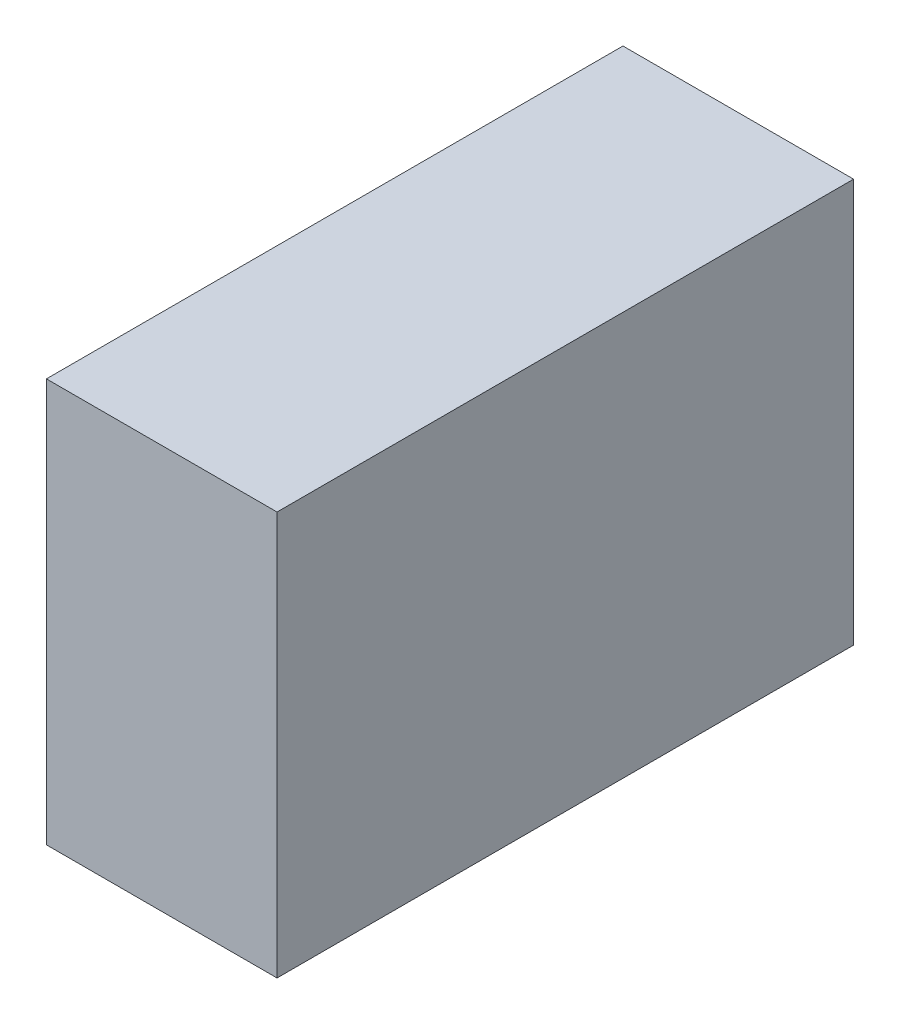
SolidWorks part; units mm, degrees
ref_plane "Front Plane" through (0, 0, 0) normal (0, 0, 1) x (1, 0, 0)
ref_plane "Top Plane" through (0, 0, 0) normal (0, 1, 0) x (1, 0, 0)
ref_plane "Right Plane" through (0, 0, 0) normal (1, 0, 0) x (0, 0, -1)
sketch "Sketch1" plane through (0, 0, 0) normal (0, 0, 1) x (1, 0, 0)
  line L1 (-10, -17.5) -> (10, -17.5)
  line L2 (-10, -17.5) -> (-10, 17.5)
  line L3 (-10, 17.5) -> (10, 17.5)
  line L4 (10, -17.5) -> (10, 17.5)
  line L5 (-10, -17.5) -> (10, 17.5) construction
  line L6 (-10, 17.5) -> (10, -17.5) construction
  point P0 (0, 0)
  dimension "D1" = 20
  dimension "D2" = 35
extrude "Boss-Extrude1" add sketch "Sketch1" along normal blind 50
